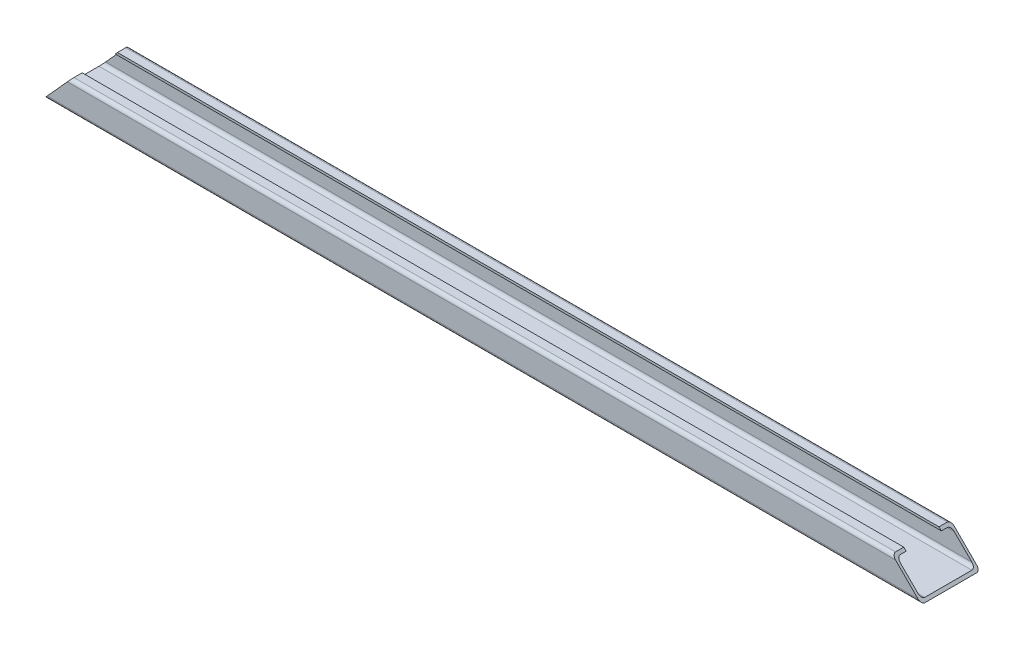
SolidWorks part; units mm, degrees
material "AISI 1045 Aço, trefilado"
ref_plane "Plano frontal" through (0, 0, 0) normal (0, 0, 1) x (1, 0, 0)
ref_plane "Plano superior" through (0, 0, 0) normal (0, 1, 0) x (1, 0, 0)
ref_plane "Plano direito" through (0, 0, 0) normal (1, 0, 0) x (0, 0, -1)
sketch "Esboço1" plane through (0, 0, 0) normal (1, 0, 0) x (0, 0, -1)
  line L0 (-46, 21) -> (-46, -21)
  line L1 (-50, 25) -> (-30, 25)
  line L2 (-50, 25) -> (-50, -25)
  line L3 (-50, -25) -> (50, -25)
  line L4 (50, 25) -> (50, -25)
  line L5 (-50, 25) -> (50, -25) construction
  line L6 (-50, -25) -> (50, 25) construction
  line L7 (-46, -21) -> (46, -21)
  line L8 (46, 21) -> (46, -21)
  line L9 (-46, 21) -> (-30, 21)
  line L10 (-30, 25) -> (-30, 21)
  line L13 (30, 25) -> (30, 21)
  line L14 (30, 21) -> (46, 21)
  line L15 (-46, 21) -> (46, 21) construction
  line L16 (30, 25) -> (50, 25)
  line L17 (-50, 25) -> (50, 25) construction
  point P0 (0, 0)
  dimension "D1" = 100
  dimension "D2" = 50
  dimension "D4" = 20
  dimension "D5" = 20
  dimension "D3" = 4
extrude "Ressalto-extrusão1" add sketch "Esboço1" along normal blind 1500
fillet "Filete1" radius 6 8 edges at (750, 21, -46) (750, 21, 46) (750, 25, 50) (750, 25, -50) (750, -25, -50) (750, -21, -46) (750, -21, 46) (750, -25, 50)
sketch "Esboço3" plane through (0, 0, 0) normal (0, 0, 1) x (1, 0, 0)
  line L0 (0, -25) -> (184.7676, 159.7676)
  line L1 (184.7676, 159.7676) -> (-208.6154, 104.9391)
  line L2 (-208.6154, 104.9391) -> (0, -25)
  line L3 (0, 19) -> (0, -19) construction
  line L4 (1500, -25) -> (1327.7073, 147.2927)
  line L5 (1327.7073, 147.2927) -> (1799.3834, 147.2927)
  line L6 (1799.3834, 147.2927) -> (1500, -25)
  line L7 (1500, -25) -> (0, -25) construction
  dimension "D1" = 45
  dimension "D2" = 45
extrude "Corte-extrusão1" cut sketch "Esboço3" against normal mid plane 100
sketch "Esboço4" plane through (0, 0, 0) normal (0, 0, 1) x (1, 0, 0)
  line L4 (50, 25) -> (-16.2356, -48.5621)
  line L5 (-16.2356, -48.5621) -> (-42.1297, -17.7158)
  line L6 (-42.1297, -17.7158) -> (50, 25)
  line L7 (6, -19) -> (44, 19) construction
  dimension "D1" = 3
extrude "Corte-extrusão2" cut sketch "Esboço4" against normal mid plane 100
